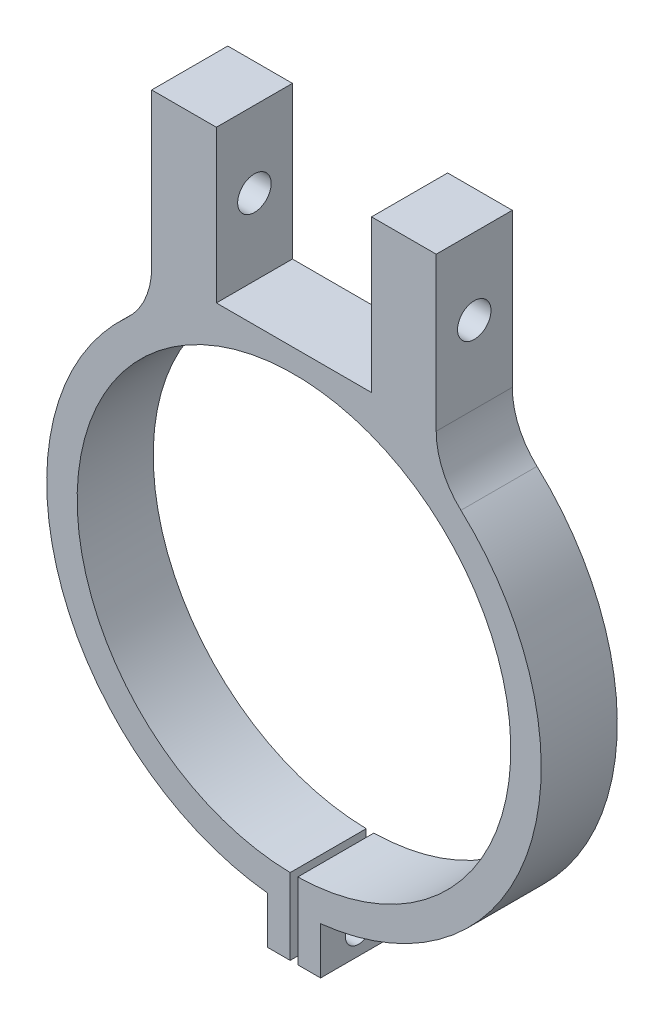
SolidWorks part; units mm, degrees
ref_plane "Ebene vorne" through (0, 0, 0) normal (0, 0, 1) x (1, 0, 0)
ref_plane "Ebene oben" through (0, 0, 0) normal (0, 1, 0) x (1, 0, 0)
ref_plane "Ebene rechts" through (0, 0, 0) normal (1, 0, 0) x (0, 0, -1)
sketch "Skizze1" plane through (0, 0, 0) normal (0, 0, 1) x (1, 0, 0)
  line L0 (0, 0) -> (0, 53.7291) construction
  line L14 (0, 0) -> (0, -44.1347) construction
  line L15 (0.5, -28.4956) -> (0.5, -32.4962)
  line L16 (-0.5, -28.4956) -> (-0.5, -32.4962)
  line L17 (0.5, -32.4962) -> (0.5, -38.4962)
  line L18 (0.5, -38.4962) -> (3.5, -38.4962)
  line L19 (3.5, -38.4962) -> (3.5, -32.311)
  line L20 (-3.5, -38.4962) -> (-3.5, -32.311)
  line L21 (-0.5, -38.4962) -> (-3.5, -38.4962)
  line L22 (-0.5, -32.4962) -> (-0.5, -38.4962)
  line L23 (-10.2, 31.5) -> (-10.2, 51.5)
  line L24 (-10.2, 51.5) -> (-18.7, 51.5)
  line L25 (-18.7, 51.5) -> (-18.7, 26.5812)
  line L26 (-10.2, 31.5) -> (10.2, 31.5)
  line L27 (0, 28.5) -> (12.0002, 28.5) construction
  line L28 (18.7, 51.5) -> (18.7, 26.5812)
  line L29 (10.2, 51.5) -> (18.7, 51.5)
  line L30 (10.2, 31.5) -> (10.2, 51.5)
  arc A0 (0.5, -28.4956) -> (-0.5, -28.4956) centre (0, 0) ccw
  arc A1 (-18.7, 26.5812) -> (-3.5, -32.311) centre (0, 0) ccw
  arc A2 (3.5, -32.311) -> (18.7, 26.5812) centre (0, 0) ccw
  point P10 (0, 33.5025)
  point P11 (0, 31.6594)
  point P17 (0, 31.5)
  point P18 (0, 39.6025)
  dimension "D1" = 57
  dimension "D2" = 4
  dimension "D3" = 20.4
  dimension "D4" = 20
  dimension "D5" = 3
  dimension "D6" = 8.5
  dimension "D10" = 1
  dimension "D11" = 3
  dimension "D12" = 6
extrude "Aufsatz-Linear austragen1" add sketch "Skizze1" along normal blind 10
sketch "Skizze2" plane through (-3.5, 0, 0) normal (-1, 0, 0) x (0, 0, 1)
  line L0 (0, -35.4036) -> (10, -35.4036) construction
  line L1 (0, -32.311) -> (0, -38.4962) construction
  line L2 (10, -32.311) -> (10, -38.4962) construction
  circle A0 centre (5, -35.4036) radius 1.75
  dimension "D1" = 3.5
extrude "Schnitt-Linear austragen1" cut sketch "Skizze2" against normal through all
sketch "Skizze3" plane through (0, 0, 10) normal (0, 0, 1) x (1, 0, 0)
  line L0 (-10.8174, 36.4205) -> (0, 26.8755)
  line L1 (0, 26.8755) -> (11.8484, 37.1414)
  line L2 (11.8484, 37.1414) -> (47.3746, 17.8863)
  line L3 (47.3746, 17.8863) -> (51.4546, -59.0738)
  line L4 (51.4546, -59.0738) -> (-81.1349, -43.2704)
  line L5 (-81.1349, -43.2704) -> (-40.9452, 68.8874)
  line L6 (-40.9452, 68.8874) -> (-10.8174, 36.4205)
extrude "Schnitt-Linear austragen2" [suppressed] cut sketch "Skizze3" against normal through all
sketch "Skizze4" plane through (-18.7, 0, 0) normal (-1, 0, 0) x (0, 0, 1)
  line L0 (5, 51.5) -> (5, 31.5) construction
  line L1 (10, 51.5) -> (0, 51.5) construction
  line L3 (10, 31.5) -> (0, 31.5) construction
  circle A0 centre (5, 41.5) radius 2.2
  dimension "D1" = 4.4
extrude "Schnitt-Linear austragen3" cut sketch "Skizze4" against normal through all
fillet "Verrundung1" radius 10 2 edges at (18.7, 26.5812, 5) (-18.7, 26.5812, 5)
